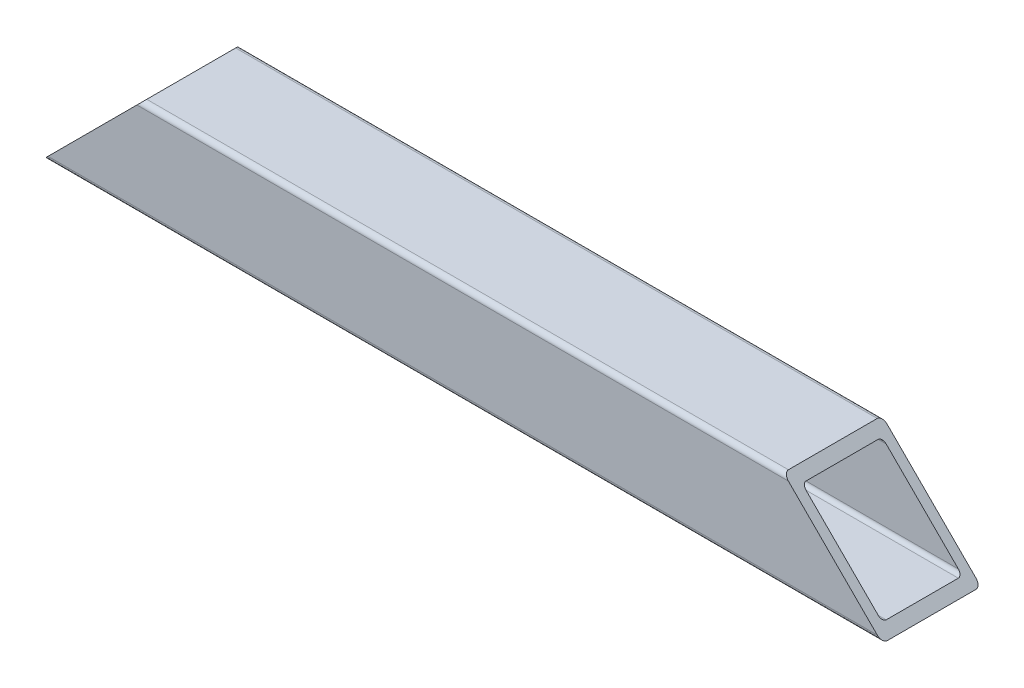
SolidWorks part; units mm, degrees
ref_plane "Front Plane" through (0, 0, 0) normal (0, 0, 1) x (1, 0, 0)
ref_plane "Top Plane" through (0, 0, 0) normal (0, 1, 0) x (1, 0, 0)
ref_plane "Right Plane" through (0, 0, 0) normal (1, 0, 0) x (0, 0, -1)
sketch "Sketch1" plane through (0, 0, 0) normal (0, 0, 1) x (1, 0, 0)
  line L0 (0, 0) -> (-431.8, 0)
  dimension "D1" = 431.8
other "Square tube 2X2X188 A500(1)"
ref_plane "Plane1" through (0, 0, 0) normal (-1, 0, 0) x (0, -1, 0)
sketch "Sketch12" plane through (0, 0, 0) normal (-1, 0, 0) x (0, -1, 0)
  line L0 (-20.6248, 0) -> (-25.4, 0) construction
  line L1 (22.86, -25.4) -> (-22.86, -25.4)
  line L2 (25.4, -22.86) -> (25.4, 22.86)
  line L3 (22.86, 25.4) -> (-22.86, 25.4)
  line L4 (-25.4, -22.86) -> (-25.4, 22.86)
  line L5 (25.4, -25.4) -> (-25.4, 25.4) construction
  line L6 (25.4, 25.4) -> (-25.4, -25.4) construction
  line L7 (18.5623, 20.6248) -> (-18.5623, 20.6248)
  line L8 (20.6248, 18.5623) -> (20.6248, -18.5623)
  line L9 (18.5623, -20.6248) -> (-18.5623, -20.6248)
  line L10 (-20.6248, 18.5623) -> (-20.6248, -18.5623)
  line L11 (20.6248, 20.6248) -> (-20.6248, -20.6248) construction
  line L12 (20.6248, -20.6248) -> (-20.6248, 20.6248) construction
  line L13 (0, -20.6248) -> (0, -25.4) construction
  line L14 (20.6248, -18.5623) -> (20.6248, -25.4) construction
  line L15 (20.6248, 0) -> (25.4, 0) construction
  line L16 (20.6248, -25.4) -> (25.4, -25.4) construction
  arc A0 (-18.5623, -20.6248) -> (-20.6248, -18.5623) centre (-18.5623, -18.5623) cw
  arc A1 (20.6248, -18.5623) -> (18.5623, -20.6248) centre (18.5623, -18.5623) cw
  arc A2 (18.5623, 20.6248) -> (20.6248, 18.5623) centre (18.5623, 18.5623) cw
  arc A3 (-18.5623, 20.6248) -> (-20.6248, 18.5623) centre (-18.5623, 18.5623) ccw
  arc A4 (22.86, -25.4) -> (25.4, -22.86) centre (22.86, -22.86) ccw
  arc A5 (25.4, 22.86) -> (22.86, 25.4) centre (22.86, 22.86) ccw
  arc A6 (-22.86, 25.4) -> (-25.4, 22.86) centre (-22.86, 22.86) ccw
  arc A7 (-22.86, -25.4) -> (-25.4, -22.86) centre (-22.86, -22.86) cw
  point P0 (0, 0)
  point P6 (0, 0)
  point P44 (0, 0)
  dimension "D2" = 2.0625
  dimension "D3" = 2.54
  dimension "D1" = 41.2496
  dimension "Outside Width" = 50.8
  dimension "Ouside Height" = 50.8
  dimension "Wall Thickness" = 4.7752
sketch "Sketch14" plane through (0, 0, 25.4) normal (0, 0, 1) x (1, 0, 0)
  line L0 (-431.8, -25.4) -> (-431.8, 25.4)
  line L1 (-431.8, -25.4) -> (-381, 25.4)
  line L2 (-431.8, 25.4) -> (0, 25.4) construction
  line L3 (-381, 25.4) -> (-431.8, 25.4)
  line L4 (0, 0) -> (-431.8, 0)
  line L5 (-215.9, 0) -> (-215.9, 18.0899) construction
  line L6 (0, -25.4) -> (0, 25.4)
  line L7 (-50.8, 25.4) -> (0, 25.4)
  line L8 (0, -25.4) -> (-50.8, 25.4)
  line M5 (0, -22.86) -> (0, 22.86)
  line M6 (0, 22.86) -> (-431.8, 22.86)
  line M7 (-431.8, 22.86) -> (-431.8, -22.86)
  line M8 (-431.8, -22.86) -> (0, -22.86)
  dimension "D1" = 45
extrude "Cut-Extrude1" cut sketch "Sketch14" against normal through all contours L4 L1 M6 M7 | L1 L4 L0 M8 | L8 L4 M5 M6 | L8 L4 M8 M5
equation "\"D3@Sketch12\"=\"Outside Width@Sketch12\"*.05"
equation "\"D2@Sketch12\"=\"D1@Sketch12\"*.05"
